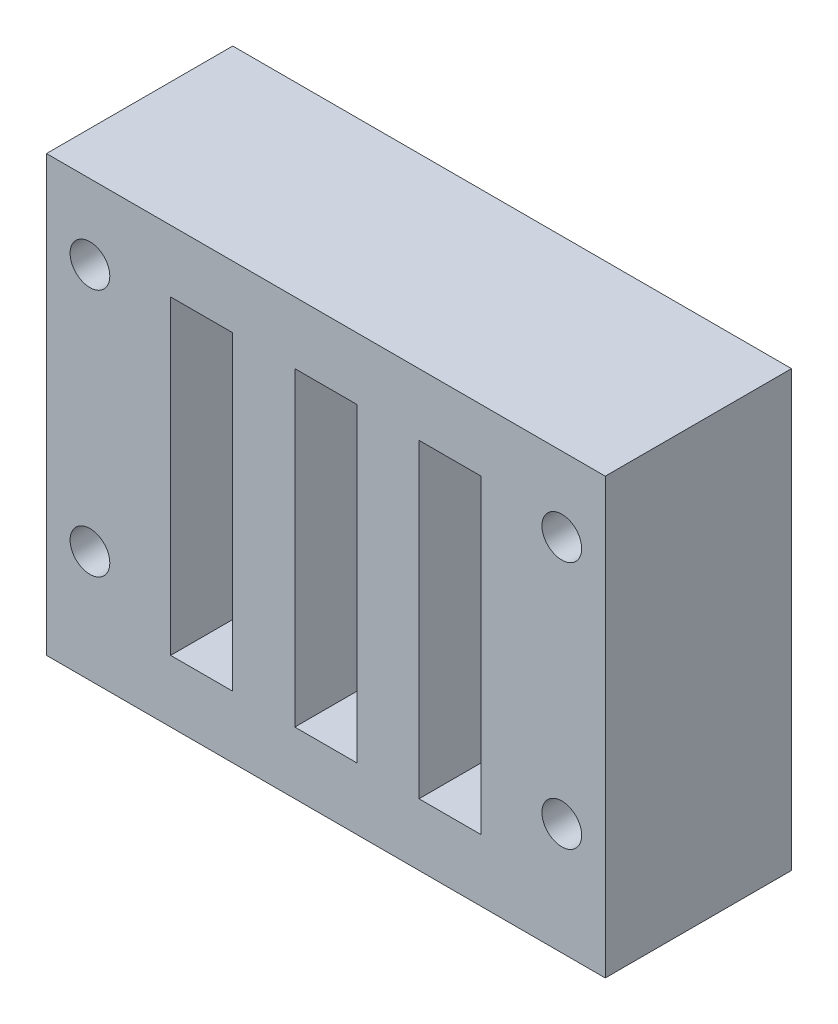
SolidWorks part; units mm, degrees
ref_plane "前视基准面" through (0, 0, 0) normal (0, 0, 1) x (1, 0, 0)
ref_plane "上视基准面" through (0, 0, 0) normal (0, 1, 0) x (1, 0, 0)
ref_plane "右视基准面" through (0, 0, 0) normal (1, 0, 0) x (0, 0, -1)
sketch "草图1" plane through (0, 0, 0) normal (0, 0, 1) x (1, 0, 0)
  line L1 (-19, 10) -> (19, 10) construction
  line L2 (-19, 10) -> (-19, -10) construction
  line L3 (-19, -10) -> (19, -10) construction
  line L4 (19, 10) -> (19, -10) construction
  line L5 (-19, 10) -> (19, -10) construction
  line L6 (-19, -10) -> (19, 10) construction
  line L7 (-22.5, 16) -> (22.5, 16)
  line L8 (-22.5, 16) -> (-22.5, -19)
  line L9 (-22.5, -19) -> (22.5, -19)
  line L10 (22.5, 16) -> (22.5, -19)
  line L11 (-22.5, 16) -> (22.5, -19) construction
  line L12 (-22.5, -19) -> (22.5, 16) construction
  circle A0 centre (-19, 10) radius 1.6
  circle A1 centre (19, 10) radius 1.6
  circle A2 centre (19, -10) radius 1.6
  circle A3 centre (-19, -10) radius 1.6
  point P0 (0, 0)
  point P8 (0, -1.5)
  point P18 (0, -3.2468)
  dimension "D3" = 3.2
  dimension "D8" = 6
  dimension "D1" = 38
  dimension "D2" = 20
  dimension "D6" = 35
  dimension "D7" = 45
  dimension "D4" = 2
  dimension "D5" = 2
extrude "凸台-拉伸1" add sketch "草图1" along normal blind 15
sketch "草图2" plane through (0, 0, 0) normal (0, 0, 1) x (1, 0, 0)
  line L0 (-22.5, -1.5) -> (22.5, -1.5) construction
  line L1 (-22.5, 16) -> (-22.5, -19) construction
  line L2 (22.5, -19) -> (22.5, 16) construction
  line L3 (0, 11) -> (0, -14)
  line L4 (10, 11) -> (10, -14)
  line L5 (-10, 11) -> (-10, -14)
  point P4 (0, 0)
  dimension "D1" = 25
  dimension "D2" = 2
  dimension "D3" = 2
extrude "切除-拉伸-薄壁2" cut sketch "草图2" along normal blind 15 thin thin type mid plane wall 5
